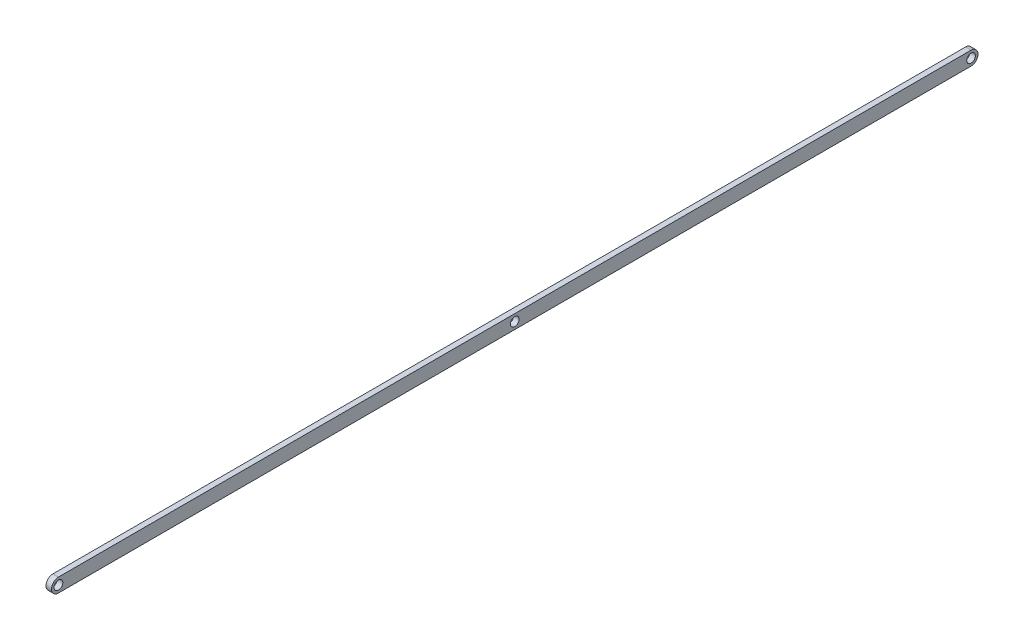
SolidWorks part; units mm, degrees
ref_plane "Front Plane" through (0, 0, 0) normal (0, 0, 1) x (1, 0, 0)
ref_plane "Top Plane" through (0, 0, 0) normal (0, 1, 0) x (1, 0, 0)
ref_plane "Right Plane" through (0, 0, 0) normal (1, 0, 0) x (0, 0, -1)
sketch "Sketch1" plane through (0, 0, 0) normal (1, 0, 0) x (0, 0, -1)
  line L0 (0, 6.35) -> (838.2, 6.35)
  line L2 (838.2, -6.35) -> (0, -6.35)
  arc A0 (0, -6.35) -> (0, 6.35) centre (0, 0) cw
  arc A1 (838.2, -6.35) -> (838.2, 6.35) centre (838.2, 0) ccw
  dimension "D1" = 12.7
  dimension "D2" = 838.2
extrude "Boss-Extrude1" add sketch "Sketch1" along normal blind 5.08
hole_wizard "Ø8.0mm Dowel Hole1" positions "Sketch4" profile "Sketch3" hole size "Ø8.0" standard "ANSI Metric" end condition through all
sketch "Sketch4" plane through (5.08, 0, 0) normal (1, 0, 0) x (0, 0, -1)
  line L1 (419.1, 6.35) -> (419.1, -6.35) construction
  line L2 (838.2, 6.35) -> (0, 6.35) construction
  line L3 (0, -6.35) -> (838.2, -6.35) construction
  arc A0 (0, 6.35) -> (0, -6.35) centre (0, 0) ccw construction
  arc A1 (838.2, -6.35) -> (838.2, 6.35) centre (838.2, 0) ccw construction
  point P0 (0, 0)
  point P2 (838.2, 0)
  point P12 (419.1, 0)
sketch "Sketch3" plane through (5.08, 0, 0) normal (0, 1, 0) x (0, 0, -1)
  line L0 (0, 0) -> (0, 5.08)
  line L1 (0, 5.08) -> (4, 5.08)
  line L2 (4, 5.08) -> (4, 0)
  line L5 (4, 0) -> (0, 0)
  line L11 (0, -6.35) -> (0, 107.95) construction
  dimension "Thru Hole Dia." = 8
  dimension "Thru Hole Depth" = 5.08
